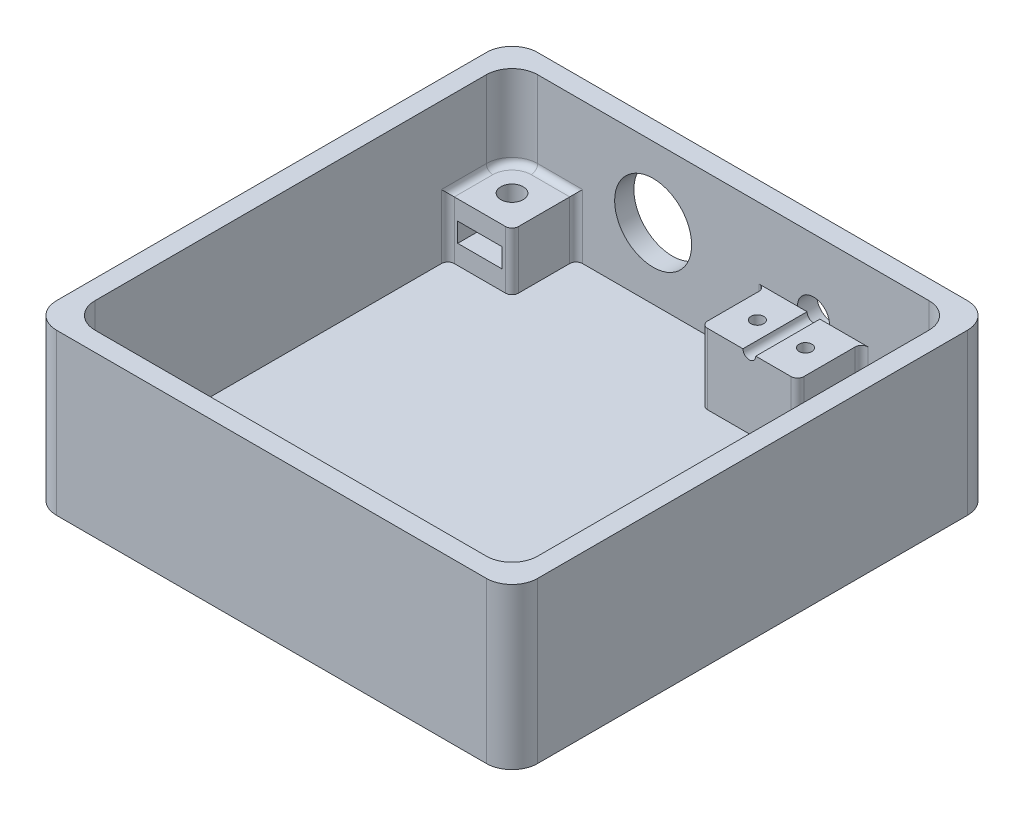
SolidWorks part; units mm, degrees
ref_plane "前视基准面" through (0, 0, 0) normal (0, 0, 1) x (1, 0, 0)
ref_plane "上视基准面" through (0, 0, 0) normal (0, 1, 0) x (1, 0, 0)
ref_plane "右视基准面" through (0, 0, 0) normal (1, 0, 0) x (0, 0, -1)
sketch "草图1" plane through (0, 0, 0) normal (0, 1, 0) x (1, 0, 0)
  line L1 (-37.5, 37.5) -> (37.5, 37.5)
  line L2 (-37.5, 37.5) -> (-37.5, -37.5)
  line L3 (-37.5, -37.5) -> (37.5, -37.5)
  line L4 (37.5, 37.5) -> (37.5, -37.5)
  line L5 (-37.5, 37.5) -> (37.5, -37.5) construction
  line L6 (-37.5, -37.5) -> (37.5, 37.5) construction
  point P0 (0, 0)
  dimension "D1" = 75
  dimension "D2" = 75
extrude "凸台-拉伸1" add sketch "草图1" along normal blind 25
shell "抽壳1" thickness 3
sketch "草图3" plane through (0, 3, 0) normal (0, 1, 0) x (1, 0, 0)
  line L7 (-34.5, -34.5) -> (-24.5, -34.5)
  line L8 (-34.5, -34.5) -> (-34.5, -24.5)
  line L9 (-34.5, -24.5) -> (-24.5, -24.5)
  line L10 (-24.5, -34.5) -> (-24.5, -24.5)
  line L11 (34.5, -34.5) -> (24.5, -34.5)
  line L12 (34.5, -34.5) -> (34.5, -24.5)
  line L13 (34.5, -24.5) -> (24.5, -24.5)
  line L14 (24.5, -34.5) -> (24.5, -24.5)
  line L15 (34.5, 34.5) -> (24.5, 34.5)
  line L16 (34.5, 34.5) -> (34.5, 24.5)
  line L17 (34.5, 24.5) -> (24.5, 24.5)
  line L18 (24.5, 34.5) -> (24.5, 24.5)
  line L19 (-34.5, 34.5) -> (-24.5, 34.5)
  line L20 (-34.5, 34.5) -> (-34.5, 24.5)
  line L21 (-34.5, 24.5) -> (-24.5, 24.5)
  line L22 (-24.5, 34.5) -> (-24.5, 24.5)
  dimension "D1" = 10
  dimension "D2" = 10
extrude "凸台-拉伸2" add sketch "草图3" along normal blind 9
sketch "草图4" plane through (0, 12, 0) normal (0, 1, 0) x (1, 0, 0)
  line L4 (-24.5, 24.5) -> (-24.5, 34.5) construction
  line L5 (-34.5, 24.5) -> (-24.5, 24.5) construction
  line L7 (24.5, -24.5) -> (24.5, -34.5) construction
  line L8 (34.5, -24.5) -> (24.5, -24.5) construction
  circle A0 centre (-29.5, 29.5) radius 1.75
  circle A1 centre (29.5, 29.5) radius 1.75
  circle A2 centre (29.5, -29.5) radius 1.75
  circle A3 centre (-29.5, -29.5) radius 1.75
  dimension "D1" = 3.5
  dimension "D2" = 5
  dimension "D3" = 5
  dimension "D4" = 5
  dimension "D5" = 5
extrude "切除-拉伸1" cut sketch "草图4" against normal up to next
sketch "草图5" plane through (0, 12, 0) normal (0, 1, 0) x (1, 0, 0)
  line L0 (24.5, 24.5) -> (34.5, 24.5) construction
  line L1 (-26.0359, 29.5) -> (-27.7679, 32.5)
  line L2 (-27.7679, 32.5) -> (-31.2321, 32.5)
  line L3 (-31.2321, 32.5) -> (-32.9641, 29.5)
  line L7 (32.9641, 29.5) -> (31.2321, 32.5)
  line L8 (31.2321, 32.5) -> (27.7679, 32.5)
  line L9 (27.7679, 32.5) -> (26.0359, 29.5)
  line L16 (26.0359, -29.5) -> (27.7679, -32.5)
  line L17 (27.7679, -32.5) -> (31.2321, -32.5)
  line L18 (31.2321, -32.5) -> (32.9641, -29.5)
  line L22 (-32.9641, -29.5) -> (-31.2321, -32.5)
  line L23 (-31.2321, -32.5) -> (-27.7679, -32.5)
  line L24 (-27.7679, -32.5) -> (-26.0359, -29.5)
  line L26 (-32.9641, 29.5) -> (-32.9641, 24.5)
  line L27 (-32.9641, 24.5) -> (-26.0359, 24.5)
  line L28 (-26.0359, 29.5) -> (-26.0359, 24.5)
  line L29 (-24.5, -24.5) -> (-34.5, -24.5) construction
  line L31 (26.0359, 29.5) -> (26.0359, 24.5)
  line L32 (26.0359, 24.5) -> (32.9641, 24.5)
  line L33 (32.9641, 29.5) -> (32.9641, 24.5)
  line L34 (34.5, -24.5) -> (24.5, -24.5) construction
  line L36 (-32.9641, -29.5) -> (-32.9641, -24.5)
  line L37 (-32.9641, -24.5) -> (-26.0359, -24.5)
  line L38 (-26.0359, -29.5) -> (-26.0359, -24.5)
  line L41 (26.0359, -29.5) -> (26.0359, -24.5)
  line L42 (26.0359, -24.5) -> (32.9641, -24.5)
  line L43 (32.9641, -29.5) -> (32.9641, -24.5)
  line L44 (-29.5, 26.5) -> (-27.7679, 26.5) [skipped]
  line L45 (-26.9019, 28) -> (-26.0359, 29.5) [skipped]
  line L46 (-32.9641, 29.5) -> (-32.0981, 28) [skipped]
  line L47 (-34.5, 24.5) -> (-24.5, 24.5) construction
  line L48 (32.0981, 28) -> (32.9641, 29.5) [skipped]
  line L49 (27.7679, 26.5) -> (29.5, 26.5) [skipped]
  line L50 (26.0359, 29.5) -> (26.9019, 28) [skipped]
  line L51 (-27.7679, -26.5) -> (-29.5, -26.5) [skipped]
  line L52 (-26.0359, -29.5) -> (-26.9019, -28) [skipped]
  line L53 (-32.0981, -28) -> (-32.9641, -29.5) [skipped]
  line L54 (31.2321, -26.5) -> (29.5, -26.5) [skipped]
  line L55 (32.9641, -29.5) -> (32.0981, -28) [skipped]
  line L56 (26.9019, -28) -> (26.0359, -29.5) [skipped]
  circle A0 centre (-29.5, 29.5) radius 3 construction
  circle A1 centre (29.5, 29.5) radius 3 construction
  circle A2 centre (29.5, -29.5) radius 3 construction
  circle A3 centre (-29.5, -29.5) radius 3 construction
  dimension "D1" = 6
  dimension "D2" = 6
  dimension "D3" = 6
  dimension "D4" = 6
extrude "切除-拉伸2" cut sketch "草图5" against normal blind 3 from offset 3 offset against normal yes
sketch "草图6" plane through (0, 0, -37.5) normal (0, 0, -1) x (-1, 0, 0)
  line L0 (-37.5, 25) -> (37.5, 25) construction
  line L1 (37.5, 25) -> (37.5, 0) construction
  circle A0 centre (12.5, 14) radius 6
  circle A1 centre (-12.5, 14) radius 2.5
  dimension "D1" = 12
  dimension "D4" = 5
  dimension "D5" = 25
  dimension "D2" = 11
  dimension "D3" = 25
extrude "切除-拉伸3" cut sketch "草图6" against normal up to next
sketch "草图7" plane through (0, 0, -34.5) normal (0, 0, 1) x (1, 0, 0)
  line L0 (37.5, 0) -> (-37.5, 0) construction
  line L1 (20, 0) -> (5, 0)
  line L2 (20, 0) -> (20, 14)
  line L3 (20, 14) -> (13.5, 14)
  line L4 (5, 0) -> (5, 14)
  line L5 (11.5, 14) -> (5, 14)
  circle A1 centre (12.5, 14) radius 2.5 construction
  arc A2 (11.5, 14) -> (13.5, 14) centre (12.5, 14) ccw
  point P8 (12.5, 0)
  dimension "D4" = 2
  dimension "D1" = 0
  dimension "D2" = 0
  dimension "D3" = 15
extrude "凸台-拉伸3" add sketch "草图7" along normal blind 10
sketch "草图8" plane through (0, 14, 0) normal (0, 1, 0) x (1, 0, 0)
  line L0 (20, 34.5) -> (20, 24.5) construction
  line L1 (20, 24.5) -> (20, 34.5) construction
  circle A0 centre (16.25, 29.5) radius 1
  circle A1 centre (8.75, 29.5) radius 1
  point P6 (20, 29.5)
  dimension "D1" = 2
  dimension "D2" = 7.5
  dimension "D3" = 3.75
extrude "切除-拉伸4" cut sketch "草图8" against normal blind 4
fillet "圆角1" radius 4 8 edges at (-34.5, 18.5, 34.5) (-34.5, 18.5, -34.5) (34.5, 18.5, 34.5) (34.5, 18.5, -34.5) (37.5, 12.5, -37.5) (-37.5, 12.5, -37.5) (-37.5, 12.5, 37.5) (37.5, 12.5, 37.5)
fillet "圆角2" radius 1 28 edges at (27.5, 12, 34.5) (33.3284, 12, 33.3284) (-27.5, 12, 34.5) (-33.3284, 12, 33.3284) (-34.5, 12, -27.5) (-33.3284, 12, -33.3284) (34.5, 12, -27.5) (33.3284, 12, -33.3284) (34.5, 12, 27.5) (24.5, 7.5, 34.5) (24.5, 7.5, 24.5) (34.5, 7.5, 24.5) (-24.5, 7.5, 34.5) (-34.5, 12, 27.5) (-34.5, 7.5, 24.5) (-24.5, 7.5, 24.5) (-34.5, 7.5, -24.5) (-24.5, 7.5, -34.5) (-24.5, 7.5, -24.5) (-27.5, 12, -34.5) (5, 8.5, -34.5) (20, 8.5, -34.5) (27.5, 12, -34.5) (24.5, 7.5, -34.5) (34.5, 7.5, -24.5) (24.5, 7.5, -24.5) (20, 8.5, -24.5) (5, 8.5, -24.5)
